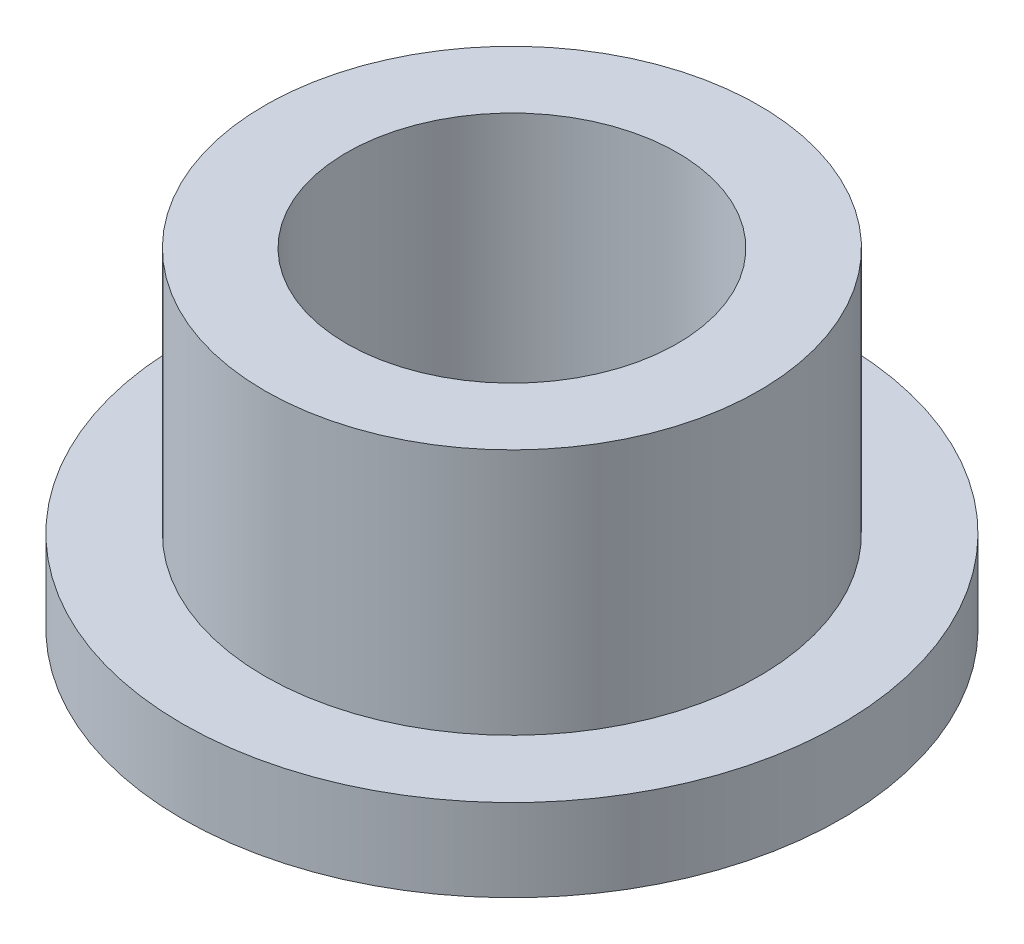
SolidWorks part; units mm, degrees
material "Phosphor bronze 10% D, UNS C52400"
ref_plane "Front" through (0, 0, 0) normal (0, 0, 1) x (1, 0, 0)
ref_plane "Top" through (0, 0, 0) normal (0, 1, 0) x (1, 0, 0)
ref_plane "Right" through (0, 0, 0) normal (1, 0, 0) x (0, 0, -1)
sketch "Sketch1" plane through (0, 0, 0) normal (0, 1, 0) x (1, 0, 0)
  circle A0 centre (0, 0) radius 6.3754
  circle A1 centre (0, 0) radius 9.525
  circle A2 centre (0, 0) radius 12.7
  dimension "ID" = 12.7508
  dimension "OD" = 19.05
  dimension "FlangeOD" = 25.4
sketch "Sketch2" plane through (0, 0, 0) normal (0, 1, 0) x (1, 0, 0)
  circle A0 centre (0, 0) radius 6.3754 construction
  circle A1 centre (0, 0) radius 9.525 construction
  circle A2 centre (0, 0) radius 6.3754
  circle A3 centre (0, 0) radius 9.525
extrude "Boss-Extrude1" add sketch "Sketch2" along normal blind 12.7
sketch "Sketch3" plane through (0, 0, 0) normal (0, 1, 0) x (1, 0, 0)
  circle A0 centre (0, 0) radius 12.7 construction
  circle A1 centre (0, 0) radius 9.525 construction
  circle A2 centre (0, 0) radius 12.7
  circle A3 centre (0, 0) radius 9.525
extrude "Boss-Extrude2" add sketch "Sketch3" along normal blind 3.175
